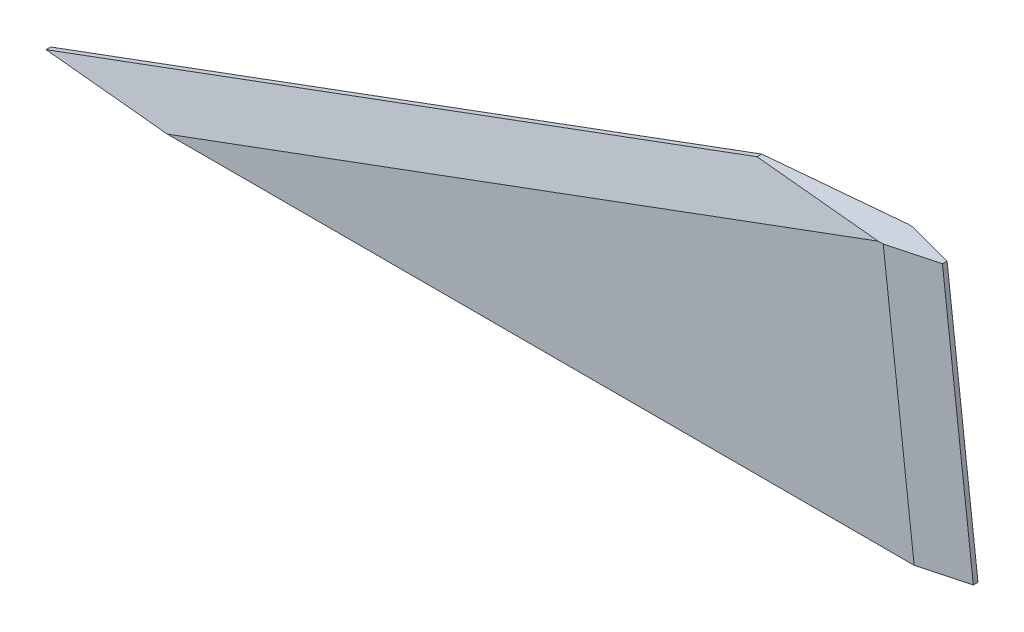
SolidWorks part; units mm, degrees
material "Wildman Fiberglass"
ref_plane "Front Plane" through (0, 0, 0) normal (0, 0, 1) x (1, 0, 0)
ref_plane "Top Plane" through (0, 0, 0) normal (0, 1, 0) x (1, 0, 0)
ref_plane "Right Plane" through (0, 0, 0) normal (1, 0, 0) x (0, 0, -1)
sketch "Sketch1" plane through (0, 0, 0) normal (0, 0, 1) x (1, 0, 0)
  line L0 (0, 0) -> (58.42, 21.59)
  line L1 (58.42, 21.59) -> (73.66, 21.59)
  line L2 (73.66, 21.59) -> (76.2, 0)
  line L3 (76.2, 0) -> (0, 0)
  dimension "D1" = 76.2
  dimension "D2" = 21.59
  dimension "D3" = 15.24
  dimension "D4" = 58.42
extrude "Boss-Extrude1" add sketch "Sketch1" along normal mid plane 2.4384
chamfer "Chamfer1" distance 3.81 distance2 1.0287 2 edges at (29.21, 10.795, 1.2192) (29.21, 10.795, -1.2192)
chamfer "Chamfer2" distance 3.81 distance2 1.0287 2 edges at (74.93, 10.795, 1.2192) (74.93, 10.795, -1.2192)
